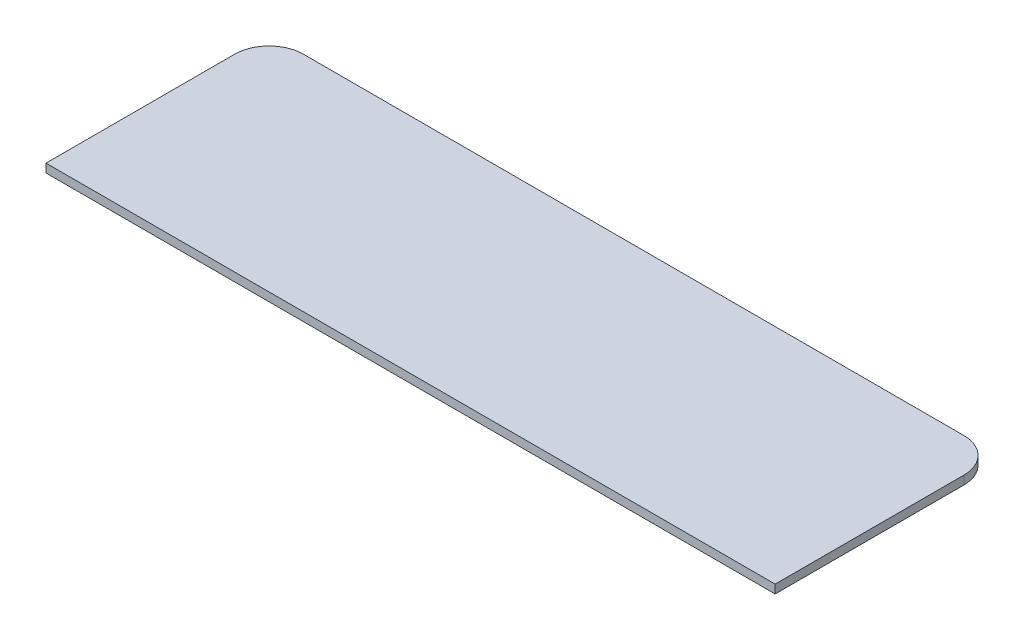
SolidWorks part; units mm, degrees
ref_plane "Front Plane" through (0, 0, 0) normal (0, 0, 1) x (1, 0, 0)
ref_plane "Top Plane" through (0, 0, 0) normal (0, 1, 0) x (1, 0, 0)
ref_plane "Right Plane" through (0, 0, 0) normal (1, 0, 0) x (0, 0, -1)
sketch "Sketch1" plane through (0, 0, 0) normal (0, 1, 0) x (1, 0, 0)
  line L1 (-38.5, 13) -> (38.5, 13)
  line L2 (-42.5, 9) -> (-42.5, -13)
  line L3 (-42.5, -13) -> (42.5, -13)
  line L4 (42.5, 9) -> (42.5, -13)
  line L5 (-42.5, 13) -> (42.5, -13) construction
  line L6 (-42.5, -13) -> (42.5, 13) construction
  arc A0 (42.5, 9) -> (38.5, 13) centre (38.5, 9) ccw
  arc A1 (-38.5, 13) -> (-42.5, 9) centre (-38.5, 9) ccw
  point P0 (0, 0)
  dimension "D3" = 4
  dimension "D1" = 85
  dimension "D2" = 26
extrude "Boss-Extrude1" add sketch "Sketch1" along normal blind 1
